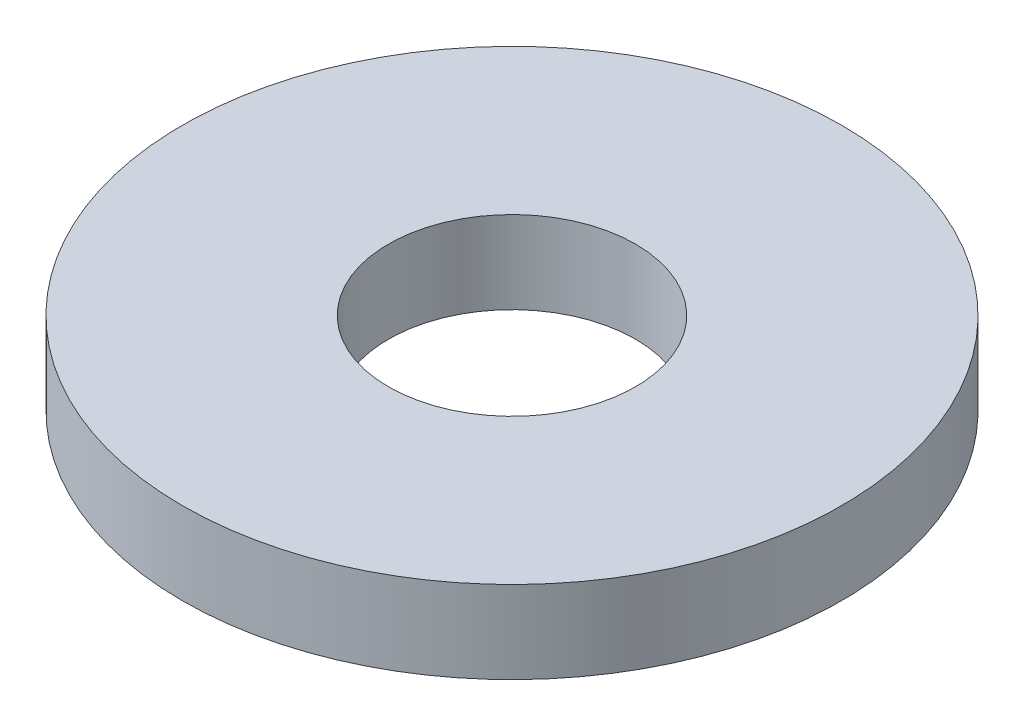
SolidWorks part; units mm, degrees
ref_plane "前视基准面" through (0, 0, 0) normal (0, 0, 1) x (1, 0, 0)
ref_plane "上视基准面" through (0, 0, 0) normal (0, 1, 0) x (1, 0, 0)
ref_plane "右视基准面" through (0, 0, 0) normal (1, 0, 0) x (0, 0, -1)
other "Configuration Table"
sketch "草图1" plane through (0, 0, 0) normal (0, 1, 0) x (1, 0, 0)
  circle A0 centre (0, 0) radius 4
  circle A1 centre (0, 0) radius 1.5
  dimension "D1" = 8
  dimension "D2" = 3
extrude "凸台-拉伸1" add sketch "草图1" along normal blind 1
